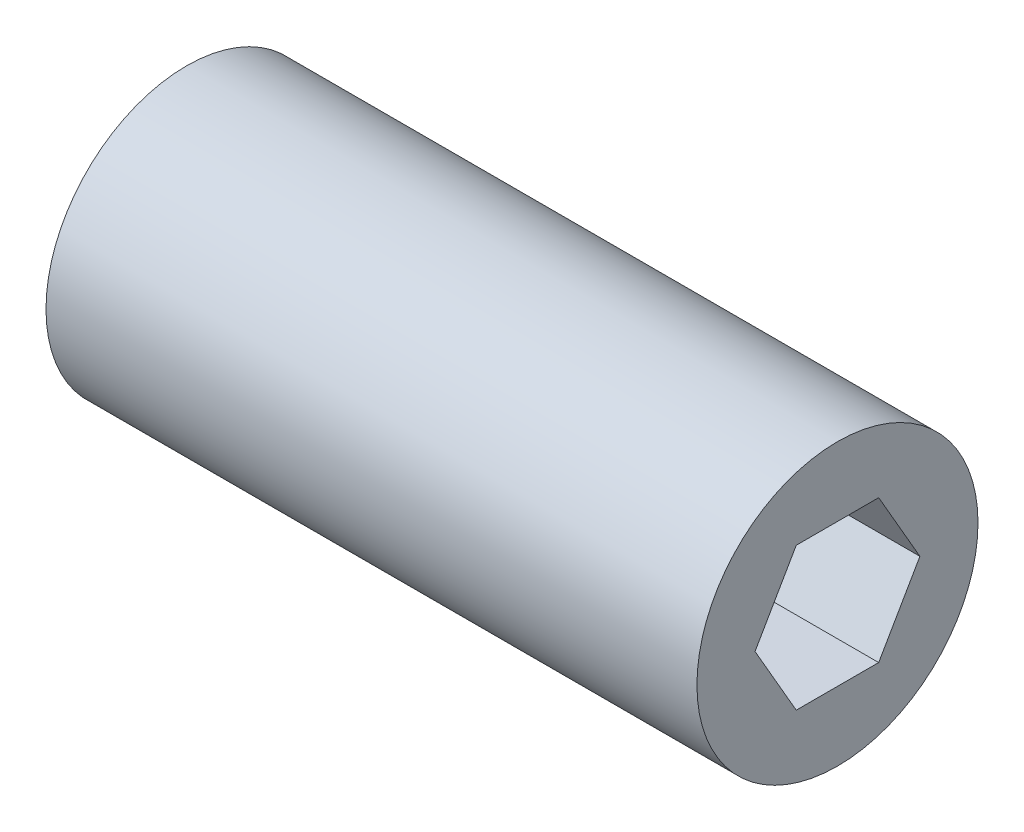
SolidWorks part; units mm, degrees
ref_plane "Alzado" through (0, 0, 0) normal (0, 0, 1) x (1, 0, 0)
ref_plane "Planta" through (0, 0, 0) normal (0, 1, 0) x (1, 0, 0)
ref_plane "Vista lateral" through (0, 0, 0) normal (1, 0, 0) x (0, 0, -1)
sketch "Croquis1" plane through (0, 0, 0) normal (1, 0, 0) x (0, 0, -1)
  line L1 (7.3323, 0) -> (3.6662, 6.35)
  line L2 (3.6662, 6.35) -> (-3.6662, 6.35)
  line L3 (-3.6662, 6.35) -> (-7.3323, 0)
  line L4 (-7.3323, 0) -> (-3.6662, -6.35)
  line L5 (-3.6662, -6.35) -> (3.6662, -6.35)
  line L6 (3.6662, -6.35) -> (7.3323, 0)
  circle A0 centre (0, 0) radius 12.5
  circle A1 centre (0, 0) radius 6.35 construction
  dimension "D2" = 25
  dimension "D1" = 12.7
extrude "Saliente-Extruir1" add sketch "Croquis1" along normal blind 57.9
